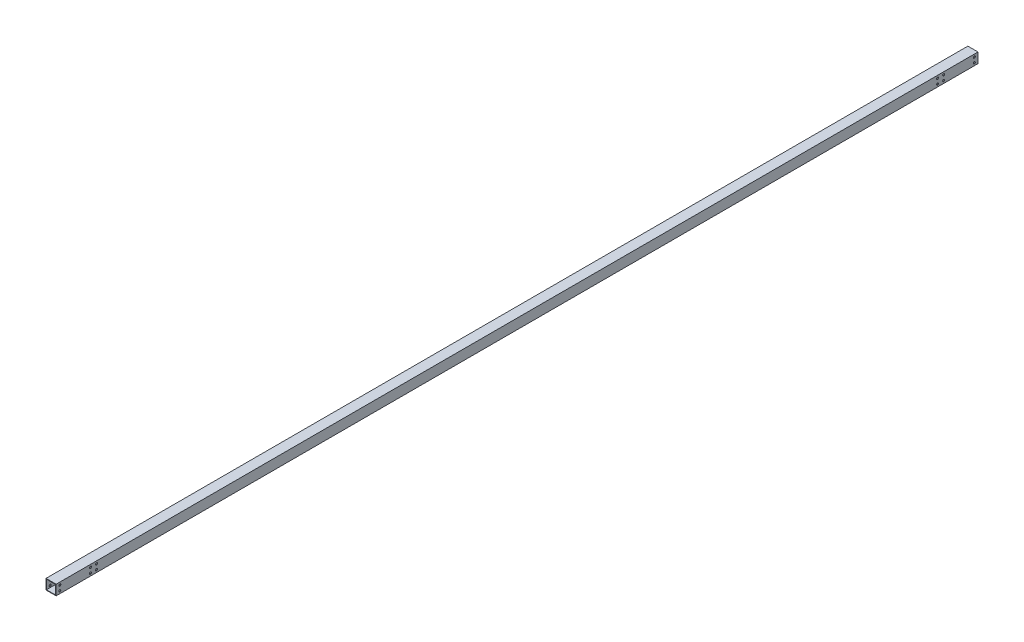
SolidWorks part; units mm, degrees
material "1100-H18 棒材(SS)"
ref_plane "前视基准面" through (0, 0, 0) normal (0, 0, 1) x (1, 0, 0)
ref_plane "上视基准面" through (0, 0, 0) normal (0, 1, 0) x (1, 0, 0)
ref_plane "右视基准面" through (0, 0, 0) normal (1, 0, 0) x (0, 0, -1)
other "Configuration Table"
sketch "草图1" plane through (0, 0, 0) normal (0, 0, 1) x (1, 0, 0)
  line L1 (0, 0) -> (20, 0)
  line L2 (0, 0) -> (0, 20)
  line L3 (0, 20) -> (20, 20)
  line L4 (20, 0) -> (20, 20)
  line L5 (1, 1) -> (19, 1)
  line L6 (1, 1) -> (1, 19)
  line L7 (1, 19) -> (19, 19)
  line L8 (19, 1) -> (19, 19)
  dimension "D1" = 20
  dimension "D2" = 20
  dimension "D3" = 1
  dimension "D4" = 1
  dimension "D5" = 1
  dimension "D6" = 1
extrude "凸台-拉伸1" add sketch "草图1" along normal blind 1820
sketch "草图2" plane through (0, 0, 0) normal (-1, 0, 0) x (0, 0, 1)
  circle A1 centre (1812.8, 5) radius 2
  circle A2 centre (1812.8, 5) radius 2
  circle A3 centre (1812.8, 15) radius 2
  circle A4 centre (1812.8, 15) radius 2
  circle A5 centre (1752.2, 15) radius 2
  circle A6 centre (1752.2, 15) radius 2
  circle A7 centre (1740.2, 15) radius 2
  circle A8 centre (1740.2, 15) radius 2
  circle A9 centre (1740.2, 5) radius 2
  circle A10 centre (1740.2, 5) radius 2
  circle A11 centre (1752.2, 5) radius 2
  circle A12 centre (1752.2, 5) radius 2
  circle A13 centre (7.2, 5) radius 2
  circle A14 centre (7.2, 5) radius 2
  circle A15 centre (7.2, 15) radius 2
  circle A16 centre (7.2, 15) radius 2
  circle A17 centre (67.8, 15) radius 2
  circle A18 centre (67.8, 15) radius 2
  circle A19 centre (79.8, 15) radius 2
  circle A20 centre (79.8, 15) radius 2
  circle A21 centre (79.8, 5) radius 2
  circle A22 centre (79.8, 5) radius 2
  circle A23 centre (67.8, 5) radius 2
  circle A24 centre (67.8, 5) radius 2
  dimension "D1" = 0
  dimension "D2" = 0
  dimension "D3" = 0
  dimension "D4" = 0
  dimension "D5" = 0
  dimension "D6" = 0
  dimension "D7" = 0
  dimension "D8" = 0
  dimension "D9" = 0
  dimension "D10" = 0
  dimension "D11" = 0
  dimension "D12" = 0
extrude "切除-拉伸1" cut sketch "草图2" against normal through all
